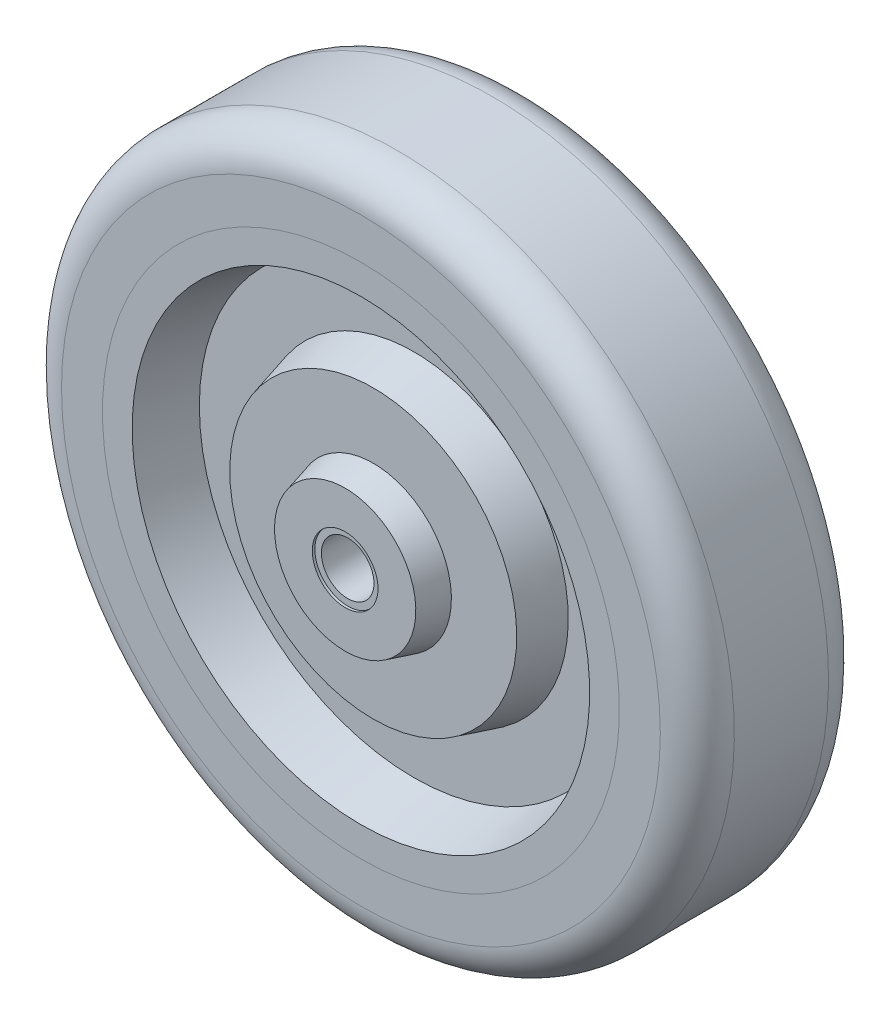
SolidWorks part; units mm, degrees
ref_plane "Front Plane" through (0, 0, 0) normal (0, 0, 1) x (1, 0, 0)
ref_plane "Top Plane" through (0, 0, 0) normal (0, 1, 0) x (1, 0, 0)
ref_plane "Right Plane" through (0, 0, 0) normal (1, 0, 0) x (0, 0, -1)
sketch "Sketch1" plane through (0, 0, 0) normal (0, 0, 1) x (1, 0, 0)
  line L0 (-3.9688, 0) -> (3.9688, 0) construction
  line L1 (-50.8, 0) -> (50.8, 0) construction
  point P3 (3.9688, 0)
  point P4 (0, 0)
  point P8 (0, 0)
  point P9 (-3.9688, 0)
  point P10 (-50.8, 0)
  point P11 (50.8, 0)
  dimension "Wheel Diameter" = 101.6
  dimension "For Axle Diameter" = 7.9375
sketch "Sketch2" plane through (0, 0, 0) normal (1, 0, 0) x (0, 0, -1)
  line L0 (-15.0812, 0) -> (15.0812, 0) construction
  line L1 (12.7, 0) -> (-12.7, 0) construction
  point P4 (0, 0)
  point P8 (0, 0)
  point P11 (0, 0)
  dimension "Hub Length" = 30.1625
  dimension "Wheel Width" = 25.4
sketch "Sketch3" plane through (0, 0, 0) normal (1, 0, 0) x (0, 0, -1)
  line L0 (0, -50.8) -> (0, 50.8) construction
  line L1 (7.112, 50.8) -> (-7.112, 50.8)
  line L2 (12.7, -50.8) -> (12.7, 50.8) construction
  line L3 (12.7, -39.0271) -> (12.7, 39.0271) construction
  line L4 (12.7, 45.212) -> (12.7, 39.0271)
  line L5 (12.7, 39.0271) -> (0, 39.0271)
  line L9 (-12.7, -50.8) -> (-12.7, 50.8) construction
  line L10 (-12.7, 45.212) -> (-12.7, 39.0271)
  line L11 (0, 39.0271) -> (-12.7, 39.0271)
  arc A4 (7.112, 50.8) -> (12.7, 45.212) centre (7.112, 45.212) cw
  arc A5 (-7.112, 50.8) -> (-12.7, 45.212) centre (-7.112, 45.212) ccw
  point P4 (0, 0)
  point P7 (0, 50.8)
  point P12 (12.7, 0)
  point P18 (12.7, 0)
  point P23 (-12.7, 0)
  dimension "D1" = 101.6
  dimension "D2" = 14.224
  dimension "D3" = 78.0542
revolve "Revolve1" add sketch "Sketch3" angle 360 about L0
sketch "Sketch4" plane through (0, 0, 0) normal (1, 0, 0) x (0, 0, -1)
  line L2 (-12.7, 39.0271) -> (12.7, 39.0271)
  line L6 (12.7, 39.0271) -> (12.7, 34.544)
  line L8 (-38.1, 39.0271) -> (-12.7, 39.0271) construction
  line L12 (12.7, -50.8) -> (12.7, 50.8) construction
  line L13 (12.7, -34.544) -> (12.7, 34.544) construction
  line L14 (12.7, 34.544) -> (4.699, 32.4001)
  line L15 (4.699, 32.4001) -> (4.699, 23.3115)
  line L16 (15.0812, -10.668) -> (15.0812, 10.668) construction
  line L22 (4.699, 23.3115) -> (10.8394, 21.6662)
  line L23 (10.8394, 21.6662) -> (10.8394, 11.8046)
  line L24 (10.8394, 11.8046) -> (15.0812, 10.668)
  line L25 (15.0812, 10.668) -> (15.0812, 3.9688)
  line L26 (15.0812, 3.9688) -> (-15.0813, 3.9688)
  line L27 (0, -50.8) -> (0, 50.8) construction
  line L28 (0, 3.9688) -> (0, 39.0271) construction
  line L29 (0, -3.9688) -> (0, 3.9688) construction
  line L30 (15.0812, 3.9688) -> (15.0812, 0) construction
  line L31 (0, 3.9688) -> (0, 39.0271) construction
  line L33 (10.8394, -21.6662) -> (10.8394, 21.6662) construction
  line L34 (-15.0812, 0) -> (15.0812, 0) construction
  line L35 (-15.0812, 10.668) -> (-15.0813, 3.9688)
  line L36 (-10.8394, 11.8046) -> (-15.0812, 10.668)
  line L37 (-10.8394, 21.6662) -> (-10.8394, 11.8046)
  line L38 (-4.699, 23.3115) -> (-10.8394, 21.6662)
  line L39 (-4.699, 32.4001) -> (-4.699, 23.3115)
  line L40 (-12.7, 34.544) -> (-4.699, 32.4001)
  line L41 (-12.7, 39.0271) -> (-12.7, 34.544)
  point P18 (15.0812, 0)
  point P23 (0, 0)
  point P24 (10.8394, 0)
  point P26 (12.7, 0)
  dimension "D1" = 7.9375
  dimension "D2" = 4.2418
  dimension "D3" = 8.001
  dimension "D4" = 15
  dimension "D5" = 15
  dimension "D6" = 69.088
  dimension "D7" = 21.336
  dimension "D8" = 43.3324
revolve "Revolve2" add sketch "Sketch4" angle 360 about L0
sketch "Sketch6" plane through (0, 0, 15.0812) normal (0, 0, 1) x (1, 0, 0)
  circle A0 centre (0, 0) radius 4.9609
  dimension "D1" = 9.9219
extrude "Cut-Extrude1" cut sketch "Sketch6" against normal blind 0.381
mirror "Mirror1" about plane through (0, 0, 0) normal (0, 0, 1) of "Cut-Extrude1"
sketch "Sketch5" plane through (0, 0, 0) normal (1, 0, 0) x (0, 0, -1)
  line L0 (-15.0812, 0) -> (-15.0812, -10.668) construction
  line L1 (12.7, 0) -> (12.7, 45.212) construction
  line L2 (12.7, 45.212) -> (-12.7, 45.212) construction
  line L3 (-12.7, 45.212) -> (-12.7, 0) construction
  line L4 (-15.0812, -10.668) -> (15.0813, -10.668) construction
  line L5 (15.0813, -10.668) -> (15.0812, 0) construction
  point P13 (12.7, 45.212)
  point P14 (-12.7, 45.212)
  point P17 (15.0813, -10.668)
  point P18 (-15.0812, -10.668)
equation "\"D1@Sketch3\" = \"Wheel Diameter@Sketch1\""
equation "\"D2@Sketch3\" = \"Wheel Width@Sketch2\" * .56"
equation "\"D1@Sketch4\" = \"For Axle Diameter@Sketch1\""
equation "\"D1@Sketch6\" = \"For Axle Diameter@Sketch1\" * 1.25"
